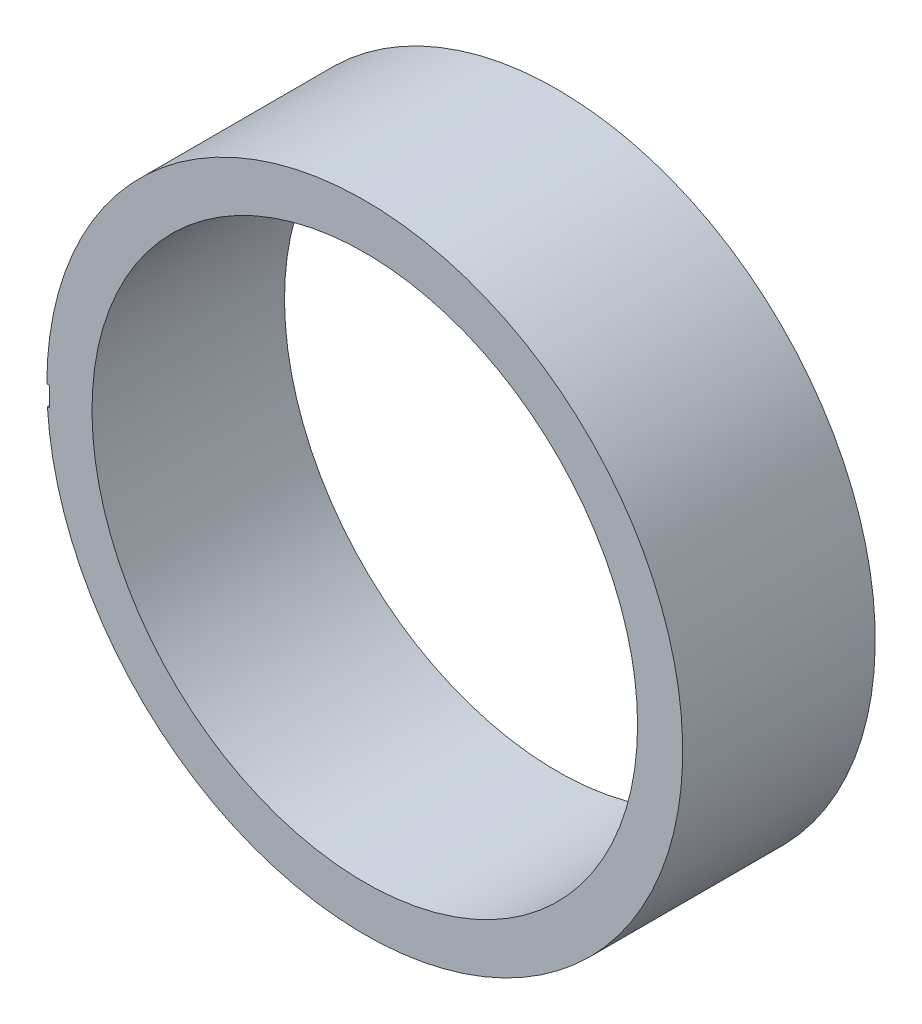
SolidWorks part; units mm, degrees
ref_plane "Front Plane" through (0, 0, 0) normal (0, 0, 1) x (1, 0, 0)
ref_plane "Top Plane" through (0, 0, 0) normal (0, 1, 0) x (1, 0, 0)
ref_plane "Right Plane" through (0, 0, 0) normal (1, 0, 0) x (0, 0, -1)
sketch "Sketch1" plane through (0, 0, 0) normal (0, 0, 1) x (1, 0, 0)
  circle A0 centre (0, 0) radius 16.5149
  circle A1 centre (0, 0) radius 14.17
  dimension "D1" = 28.34
extrude "Boss-Extrude1" add sketch "Sketch1" along normal blind 10
sketch "Sketch2" plane through (0, 0, 0) normal (0, 1, 0) x (1, 0, 0)
  line L1 (-18.1141, 1.5803) -> (-16.3658, 1.5803)
  line L2 (-18.1141, 1.5803) -> (-18.1141, -12.843)
  line L3 (-18.1141, -12.843) -> (-16.3658, -12.843)
  line L4 (-16.3658, 1.5803) -> (-16.3658, -12.843)
extrude "Cut-Extrude1" cut sketch "Sketch2" against normal blind 1
sketch "Sketch3" plane through (0, 0, 0) normal (0, 0, 1) x (1, 0, 0)
  line L1 (0.3158, 17.6913) -> (1.634, 17.6913)
  line L2 (0.3158, 17.6913) -> (0.3158, 12.3494)
  line L3 (0.3158, 12.3494) -> (1.634, 12.3494)
  line L4 (1.634, 17.6913) -> (1.634, 12.3494)
extrude "Cut-Extrude2" cut sketch "Sketch3" along normal blind 0.01
